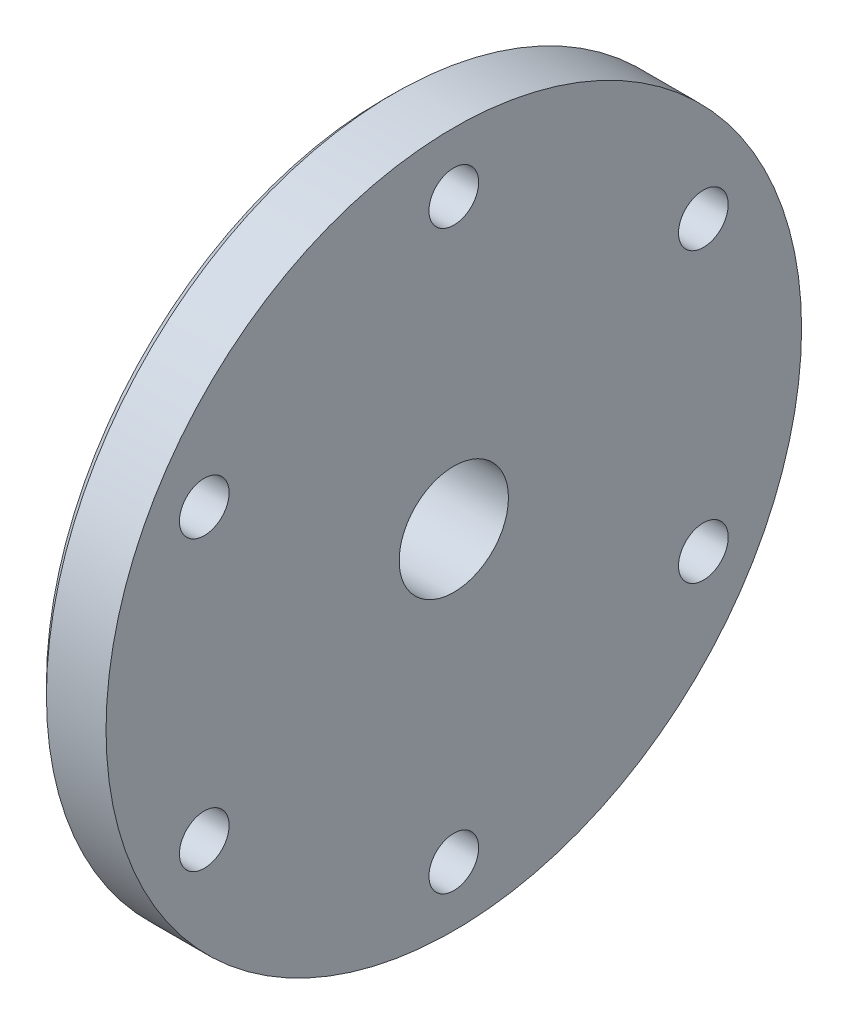
SolidWorks part; units mm, degrees
ref_plane "Piano frontale" through (0, 0, 0) normal (0, 0, 1) x (1, 0, 0)
ref_plane "Piano superiore" through (0, 0, 0) normal (0, 1, 0) x (1, 0, 0)
ref_plane "Piano destro" through (0, 0, 0) normal (1, 0, 0) x (0, 0, -1)
sketch "Schizzo1" plane through (0, 0, 0) normal (0, 1, 0) x (1, 0, 0)
  line L0 (-7, 0) -> (-12, 0)
  line L1 (0, 0) -> (-7, 0)
  line L2 (0, 0) -> (0, -35)
  line L3 (0, -35) -> (-7, -35)
  line L4 (-7, 0) -> (-7, -35)
  line L5 (-12, 0) -> (-12, -10)
  line L6 (-12, -10) -> (-7, -24)
  line L7 (-7, -24) -> (-7, 0)
  dimension "D1" = 35
  dimension "D2" = 7
  dimension "D3" = 5
  dimension "D4" = 10
  dimension "D5" = 11
revolve "Rivoluzione1" add sketch "Schizzo1" angle 360 about L1
sketch "Schizzo2" plane through (-7, 0, 0) normal (-1, 0, 0) x (0, 0, 1)
  line L0 (0, 29) -> (0, -29)
  line L1 (-29, 0) -> (29, 0)
  line L2 (25.1147, 14.5) -> (-25.1147, -14.5)
  line L3 (-25.1147, 14.5) -> (25.1147, -14.5)
  circle A0 centre (0, 0) radius 29
  circle A1 centre (0, 29) radius 2.5
  circle A2 centre (-25.1147, 14.5) radius 2.5
  circle A3 centre (-25.1147, -14.5) radius 2.5
  circle A4 centre (0, -29) radius 2.5
  circle A5 centre (25.1147, -14.5) radius 2.5
  circle A6 centre (25.1147, 14.5) radius 2.5
  dimension "D1" = 58
  dimension "D4" = 5
  dimension "D5" = 5
  dimension "D6" = 5
  dimension "D7" = 5
  dimension "D8" = 5
  dimension "D9" = 5
  dimension "D2" = 30
  dimension "D3" = 30
extrude "Taglio-Estrusione1" cut sketch "Schizzo2" against normal through all contours A0 A1 | A0 A1 L0 | L0 A1 A0 | A0 A6 L2 | L2 A6 A0 | A0 A6 | A5 | A4 | A3 | A2
sketch "Schizzo3" plane through (0, 0, 0) normal (1, 0, 0) x (0, 0, -1)
  circle A0 centre (0, 0) radius 5.5
  dimension "D1" = 11
extrude "Taglio-Estrusione2" cut sketch "Schizzo3" against normal blind 8
fillet "Raccordo1" radius 1 1 edges at (-7, 0, -24)
chamfer "Smusso1" distance 1 angle 45 1 edges at (-7, 0, -35)
